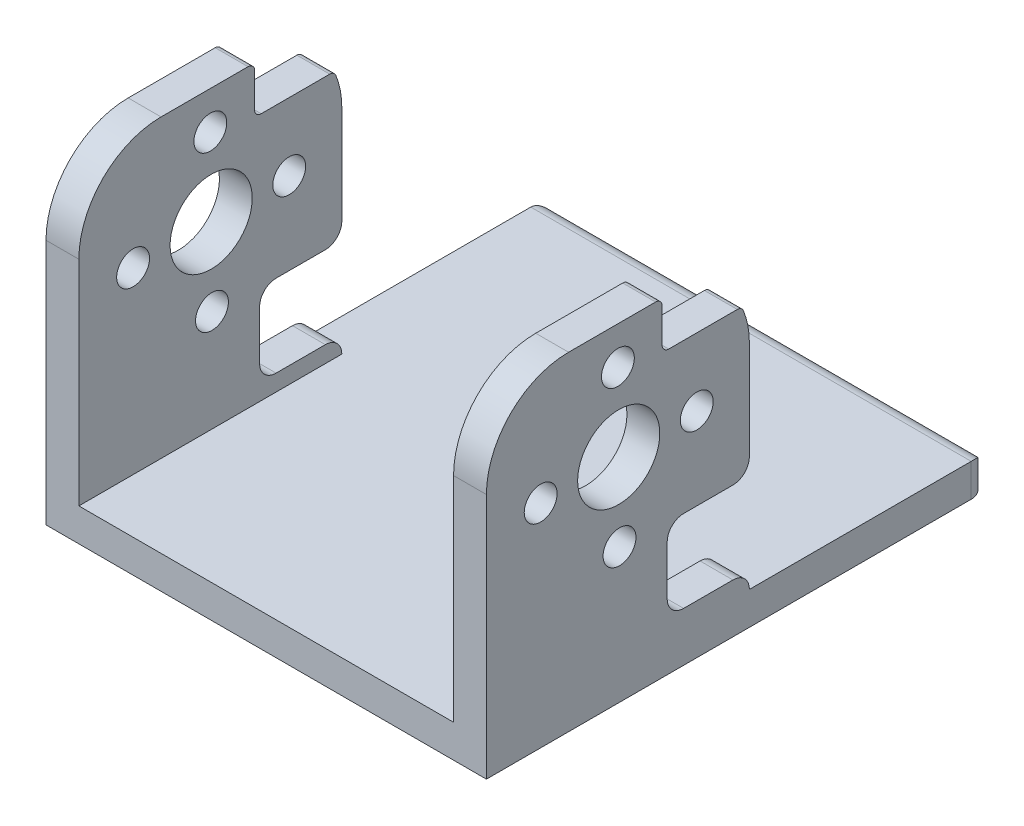
SolidWorks part; units mm, degrees
ref_plane "Front Plane" through (0, 0, 0) normal (0, 0, 1) x (1, 0, 0)
ref_plane "Top Plane" through (0, 0, 0) normal (0, 1, 0) x (1, 0, 0)
ref_plane "Right Plane" through (0, 0, 0) normal (1, 0, 0) x (0, 0, -1)
sketch "Sketch1" plane through (0, 0, 0) normal (0, 1, 0) x (1, 0, 0)
  line L1 (-17.018, -10.16) -> (17.018, -10.16)
  line L2 (-17.018, -10.16) -> (-17.018, 10.16)
  line L3 (-17.018, 10.16) -> (17.018, 10.16)
  line L4 (17.018, -10.16) -> (17.018, 10.16)
  line L5 (-17.018, -10.16) -> (17.018, 10.16) construction
  line L6 (-17.018, 10.16) -> (17.018, -10.16) construction
  point P0 (0, 0)
  dimension "D1" = 34.036
  dimension "D2" = 20.32
extrude "Boss-Extrude1" add sketch "Sketch1" along normal blind 25.4
sketch "Sketch2" plane through (0, 25.4, 0) normal (0, 1, 0) x (1, 0, 0)
  line L0 (-14.478, 10.16) -> (14.478, 10.16)
  line L1 (-14.478, 10.16) -> (-14.478, -10.16)
  line L2 (14.478, 10.16) -> (14.478, -10.16)
  line L3 (-14.478, -10.16) -> (14.478, -10.16)
  line L4 (17.018, 10.16) -> (-17.018, 10.16) construction
  line L6 (-17.018, 10.16) -> (-17.018, -10.16) construction
  line L7 (-17.018, -10.16) -> (17.018, -10.16) construction
  line L8 (17.018, -10.16) -> (17.018, 10.16) construction
  dimension "D1" = 2.54
  dimension "D2" = 2.54
extrude "Cut-Extrude1" cut sketch "Sketch2" against normal offset from surface (22.86 mm away) 2.54 up to face at (0, 0, 0)
sketch "Sketch3" plane through (-17.018, 0, 0) normal (-1, 0, 0) x (0, 0, 1)
  line L0 (0, 25.4) -> (0, 0) construction
  line L1 (-10.16, 25.4) -> (10.16, 25.4) construction
  line L2 (-7.874, 16.51) -> (7.874, 16.51) construction
  line L3 (-10.16, 0) -> (10.16, 0) construction
  circle A0 centre (-0.0635, 16.4465) radius 3.175
  circle A2 centre (0, 22.479) radius 1.27
  circle A3 centre (5.969, 16.383) radius 1.27
  circle A8 centre (0, 16.51) radius 7.874 construction
  circle A9 centre (-0.127, 10.414) radius 1.27
  circle A10 centre (-6.096, 16.51) radius 1.27
  point P18 (-0.0635, 16.4465)
  dimension "D2" = 15.748
  dimension "D3" = 5.969
  dimension "D1" = 2.54
  dimension "D5" = 6.096
  dimension "D6" = 16.51
  dimension "D7" = 6.35
  dimension "D4" = 4
extrude "Cut-Extrude2" cut sketch "Sketch3" against normal through all contours A2 | A10 | A9 | A3 | A0
sketch "Sketch4" plane through (0, 0, 0) normal (0, -1, 0) x (1, 0, 0)
  line L1 (-10.795, -9.525) -> (10.795, -9.525) construction
  line L2 (-10.795, -9.525) -> (-10.795, 9.525) construction
  line L3 (-10.795, 9.525) -> (10.795, 9.525) construction
  line L4 (17.018, -10.16) -> (17.018, 10.16)
  line L5 (17.018, 10.16) -> (-17.018, 10.16)
  line L6 (-17.018, 10.16) -> (-17.018, -10.16)
  line L7 (-17.018, -10.16) -> (17.018, -10.16)
  line L8 (17.018, -10.16) -> (17.018, 10.16) construction
  line L9 (17.018, 10.16) -> (-17.018, 10.16) construction
  line L10 (-17.018, 10.16) -> (-17.018, -10.16) construction
  line L11 (-17.018, -10.16) -> (17.018, -10.16) construction
  line L12 (10.795, -9.525) -> (10.795, 9.525) construction
  line L13 (-10.795, -9.525) -> (10.795, 9.525) construction
  line L14 (-10.795, 9.525) -> (10.795, -9.525) construction
  circle A0 centre (-10.795, 9.525) radius 1.778
  circle A1 centre (10.795, 9.525) radius 1.778
  circle A2 centre (10.795, -9.525) radius 1.778
  circle A3 centre (-10.795, -9.525) radius 1.778
  point P56 (0, 0)
  dimension "D4" = 3.556
  dimension "D2" = 19.05
  dimension "D3" = 21.59
  dimension "D1" = 0
fillet "Fillet2" radius 6.35 4 edges at (15.748, 25.4, -10.16) (15.748, 25.4, 10.16) (-15.748, 25.4, 10.16) (-15.748, 25.4, -10.16)
sketch "Sketch8" plane through (17.018, 0, 0) normal (1, 0, 0) x (0, 0, -1)
  line L0 (-10.16, 0) -> (10.16, 0) construction
  line L1 (10.16, 10.16) -> (3.81, 10.16)
  line L2 (10.16, 10.16) -> (10.16, 3.81)
  line L3 (10.16, 3.81) -> (3.81, 3.81)
  line L4 (3.81, 10.16) -> (3.81, 3.81)
  line L6 (10.16, 19.05) -> (10.16, 0) construction
  dimension "D1" = 6.35
  dimension "D2" = 6.35
  dimension "D3" = 3.81
extrude "Cut-Extrude5" cut sketch "Sketch8" against normal through all
fillet "Fillet4" radius 1.27 8 edges at (15.748, 3.81, -10.16) (15.748, 3.81, -3.81) (15.748, 10.16, -10.16) (15.748, 10.16, -3.81) (-15.748, 10.16, -10.16) (-15.748, 10.16, -3.81) (-15.748, 3.81, -3.81) (-15.748, 3.81, -10.16)
sketch "Sketch10" plane through (17.018, 0, 0) normal (1, 0, 0) x (0, 0, -1)
  line L5 (3.4225, 28.709) -> (12.2581, 28.709)
  line L6 (3.4225, 28.709) -> (3.4225, 21.7448)
  line L7 (3.4225, 21.7448) -> (12.2581, 21.7448)
  line L8 (12.2581, 28.709) -> (12.2581, 21.7448)
extrude "Cut-Extrude6" cut sketch "Sketch10" against normal through all
fillet "Fillet6" radius 0.508 3 edges at (15.748, 21.7448, -9.5598) (15.748, 25.4, -3.4225) (15.748, 21.7448, -3.4225)
fillet "Fillet7" radius 0.508 3 edges at (-15.748, 21.7448, -9.5598) (-15.748, 21.7448, -3.4225) (-15.748, 25.4, -3.4225)
sketch "Sketch11" plane through (0, 0, -10.16) normal (0, 0, -1) x (-1, 0, 0)
  line L1 (-17.018, 2.54) -> (17.018, 2.54)
  line L2 (-17.018, 2.54) -> (-17.018, 0)
  line L3 (-17.018, 0) -> (17.018, 0)
  line L4 (17.018, 2.54) -> (17.018, 0)
extrude "Boss-Extrude3" add sketch "Sketch11" along normal blind 18.415
fillet "Fillet8" radius 1.27 3 edges at (0, 2.54, -28.575) (-17.018, 1.27, -28.575) (17.018, 1.27, -28.575)
